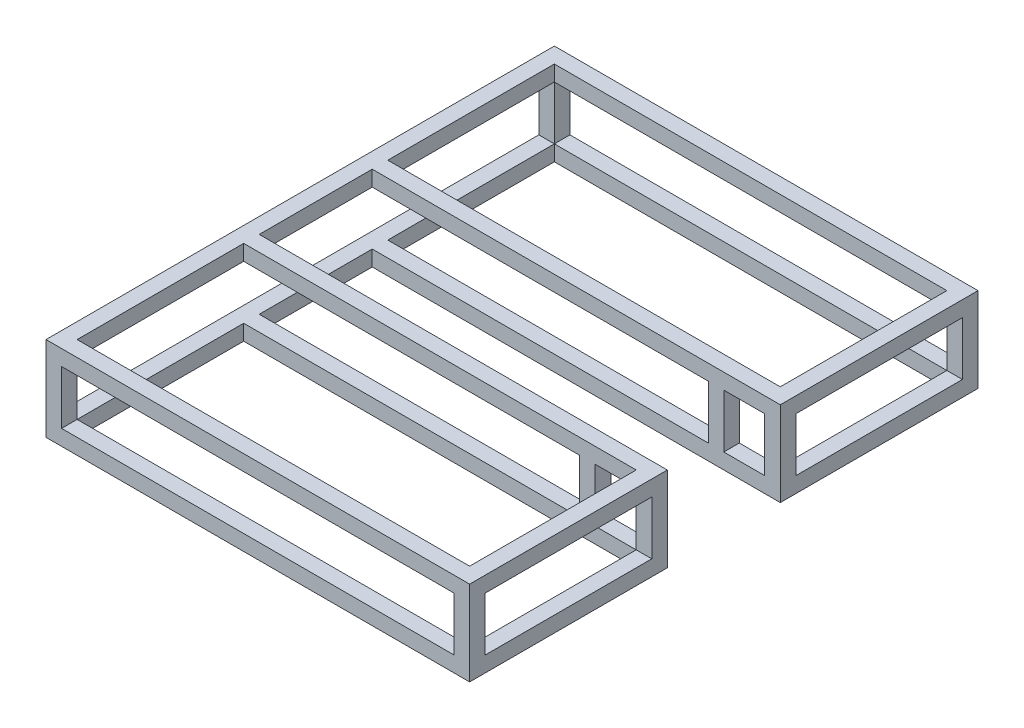
SolidWorks part; units mm, degrees
ref_plane "Front Plane" through (0, 0, 0) normal (0, 0, 1) x (1, 0, 0)
ref_plane "Top Plane" through (0, 0, 0) normal (0, 1, 0) x (1, 0, 0)
ref_plane "Right Plane" through (0, 0, 0) normal (1, 0, 0) x (0, 0, -1)
sketch "Sketch1" plane through (0, 0, 0) normal (0, 0, 1) x (1, 0, 0)
  line L1 (-190.5, 38.1) -> (190.5, 38.1)
  line L2 (-190.5, 38.1) -> (-190.5, -38.1)
  line L3 (-190.5, -38.1) -> (190.5, -38.1)
  line L4 (190.5, 38.1) -> (190.5, -38.1)
  line L5 (-190.5, 38.1) -> (190.5, -38.1) construction
  line L6 (-190.5, -38.1) -> (190.5, 38.1) construction
  point P0 (0, 0)
  dimension "D1" = 381
  dimension "D2" = 76.2
extrude "Boss-Extrude1" add sketch "Sketch1" along normal blind 14
sketch "Sketch2" plane through (0, 0, 14) normal (0, 0, 1) x (1, 0, 0)
  line L0 (176.5, -24.1) -> (176.5, 24.1)
  line L2 (176.5, -24.1) -> (-176.5, -24.1)
  line L4 (176.5, 24.1) -> (-176.5, 24.1)
  line L7 (-176.5, -24.1) -> (-176.5, 24.1)
extrude "Cut-Extrude1" cut sketch "Sketch2" against normal blind 14
sketch "Sketch3" plane through (0, 0, 14) normal (0, 0, 1) x (1, 0, 0)
  line L0 (-190.5, -38.1) -> (-190.5, -24.1)
  line L2 (-176.5, -24.1) -> (-176.5, -38.1)
  line L3 (-190.5, -38.1) -> (190.5, -38.1) construction
  line L4 (-176.5, 24.1) -> (-176.5, 38.1)
  line L5 (190.5, 38.1) -> (-190.5, 38.1) construction
  line L6 (-176.5, 38.1) -> (-190.5, 38.1)
  line L7 (-176.5, -38.1) -> (-190.5, -38.1)
  line L8 (-176.5, 24.1) -> (-190.5, 24.1)
  line L9 (176.5, -24.1) -> (176.5, -38.1)
  line L11 (176.5, 24.1) -> (176.5, 38.1)
  line L12 (176.5, 38.1) -> (190.5, 38.1)
  line L13 (190.5, -38.1) -> (190.5, -24.1)
  line L14 (176.5, -38.1) -> (190.5, -38.1)
  line L15 (-176.5, -24.1) -> (-190.5, -24.1)
  line L16 (-190.5, 24.1) -> (-190.5, 38.1)
  line L17 (176.5, 24.1) -> (190.5, 24.1)
  line L18 (176.5, -24.1) -> (190.5, -24.1)
  line L19 (190.5, 24.1) -> (190.5, 38.1)
sketch "Sketch4" plane through (0, 0, 0) normal (0, 1, 0) x (1, 0, 0)
  line L0 (-190.5, 0) -> (-190.5, -457.2) construction
  line L1 (-190.5, -228.6) -> (270.9619, -228.6) construction
  line L2 (-190.5, -443.23) -> (190.5, -443.23)
  line L3 (190.5, -457.2) -> (-190.5, -457.2)
  line L4 (-190.5, -457.2) -> (-190.5, -443.23)
  line L5 (190.5, -443.23) -> (190.5, -457.2)
ref_plane "Plane1" through (0, -38.1, 0) normal (0, 1, 0) x (1, 0, 0)
sketch "Sketch5" plane through (0, -38.1, 0) normal (0, 1, 0) x (1, 0, 0)
  line L0 (-190.5, -443.23) -> (190.5, -443.23)
  line L1 (190.5, -443.23) -> (190.5, -457.2)
  line L2 (190.5, -457.2) -> (-190.5, -457.2)
  line L3 (-190.5, -457.2) -> (-190.5, -443.23)
extrude "Boss-Extrude2" add sketch "Sketch5" along normal blind 76.2 separate body
sketch "Sketch6" plane through (0, 0, 443.23) normal (0, 0, -1) x (-1, 0, 0)
  line L0 (176.5, 24.1) -> (176.5, -24.1)
  line L1 (176.5, -24.1) -> (-176.5, -24.1)
  line L2 (-176.5, -24.1) -> (-176.5, 24.1)
  line L3 (-176.5, 24.1) -> (176.5, 24.1)
extrude "Cut-Extrude2" cut sketch "Sketch6" against normal blind 76.2
extrude "Boss-Extrude3" add sketch "Sketch3" along normal blind 429.26
sketch "Sketch7" plane through (0, 38.1, 0) normal (0, 1, 0) x (1, 0, 0)
  line L0 (190.5, -177.8) -> (176.5, -177.8)
  line L1 (190.5, -457.2) -> (190.5, 0) construction
  line L2 (190.5, -279.4) -> (176.5, -279.4)
  line L3 (176.5, -443.23) -> (176.5, -14) construction
  line L4 (190.5, -177.8) -> (190.5, -279.4)
  line L5 (176.5, -177.8) -> (176.5, -279.4)
extrude "Cut-Extrude3" cut sketch "Sketch7" against normal blind 429.26
sketch "Sketch10" plane through (0, -24.1, 0) normal (0, 1, 0) x (1, 0, 0)
  line L0 (190.5, -177.8) -> (176.5, -177.8)
  line L1 (176.5, -177.8) -> (176.5, -163.83)
  line L2 (176.5, -177.8) -> (176.5, -14) construction
  line L3 (176.5, -163.83) -> (190.5, -163.83)
  line L4 (190.5, -177.8) -> (190.5, -14) construction
  line L5 (190.5, -163.83) -> (190.5, -177.8)
  line L8 (176.5, -293.4) -> (190.5, -293.4)
  line L9 (176.5, -279.43) -> (176.5, -293.4)
  line L10 (190.5, -279.43) -> (176.5, -279.43)
  line L11 (190.5, -293.4) -> (190.5, -279.43)
extrude "Boss-Extrude4" add sketch "Sketch10" along normal blind 48.26
sketch "Sketch11" plane through (0, -38.1, 0) normal (0, 1, 0) x (1, 0, 0)
  line L0 (176.5, -177.8) -> (-176.5, -177.8)
  line L1 (-176.5, -443.23) -> (-176.5, -14) construction
  line L2 (-176.5, -177.8) -> (-176.5, -163.83)
  line L3 (-176.5, -163.83) -> (176.5, -163.83)
  line L4 (176.5, -163.83) -> (176.5, -177.8)
  line L5 (-176.5, -228.615) -> (300.5715, -228.615) construction
  line L6 (-176.5, -293.4) -> (176.5, -293.4)
  line L7 (-176.5, -279.43) -> (-176.5, -293.4)
  line L8 (176.5, -279.43) -> (-176.5, -279.43)
  line L9 (176.5, -293.4) -> (176.5, -279.43)
extrude "Boss-Extrude5" add sketch "Sketch11" along normal blind 76.2
sketch "Sketch12" plane through (0, 0, 163.83) normal (0, 0, -1) x (-1, 0, 0)
  line L0 (176.5, 24.1) -> (176.5, -24.1)
  line L1 (176.5, -24.1) -> (-176.5, -24.1)
  line L2 (-176.5, -24.1) -> (-176.5, 24.1)
  line L3 (-176.5, 24.1) -> (176.5, 24.1)
extrude "Cut-Extrude4" cut sketch "Sketch12" against normal through all both and the other way through all
sketch "Sketch13" plane through (0, -24.1, 0) normal (0, 1, 0) x (1, 0, 0)
  line L0 (139.67, -293.4) -> (125.7, -293.4)
  line L1 (176.5, -293.4) -> (-176.5, -293.4) construction
  line L2 (125.7, -293.4) -> (125.7, -279.43)
  line L3 (-176.5, -279.43) -> (176.5, -279.43) construction
  line L4 (125.7, -279.43) -> (139.67, -279.43)
  line L5 (139.67, -279.43) -> (139.67, -293.4)
  line L6 (-176.5, -228.615) -> (271.0145, -228.615) construction
  line L7 (-176.5, -279.43) -> (-176.5, -177.8) construction
  line L8 (139.67, -177.8) -> (139.67, -163.83)
  line L9 (125.7, -177.8) -> (139.67, -177.8)
  line L10 (125.7, -163.83) -> (125.7, -177.8)
  line L11 (139.67, -163.83) -> (125.7, -163.83)
extrude "Boss-Extrude6" add sketch "Sketch13" along normal blind 48.26
sketch "Sketch16" plane through (139.67, 0, 0) normal (1, 0, 0) x (0, 0, -1)
  line L7 (-228.615, 38.1) -> (-228.615, -48.8222) construction
  line L8 (-279.43, 38.1) -> (-177.8, 38.1) construction
  line L13 (-177.8, -11.4) -> (-177.8, 2.57)
  line L14 (-279.43, 24.1) -> (-279.43, -24.1) construction
  line L15 (-279.43, -11.4) -> (-293.4, -11.4)
  line L16 (-293.4, 24.1) -> (-293.4, -24.1) construction
  line L17 (-279.43, 2.57) -> (-293.4, 1.9949)
  line L18 (-293.4, 1.9949) -> (-293.4, -11.4)
  line L19 (-279.43, -11.4) -> (-279.43, 2.57)
  line L20 (-177.8, -11.4) -> (-163.83, -11.4)
  line L21 (-163.83, 1.9949) -> (-163.83, -11.4)
  line L22 (-177.8, 2.57) -> (-163.83, 1.9949)
